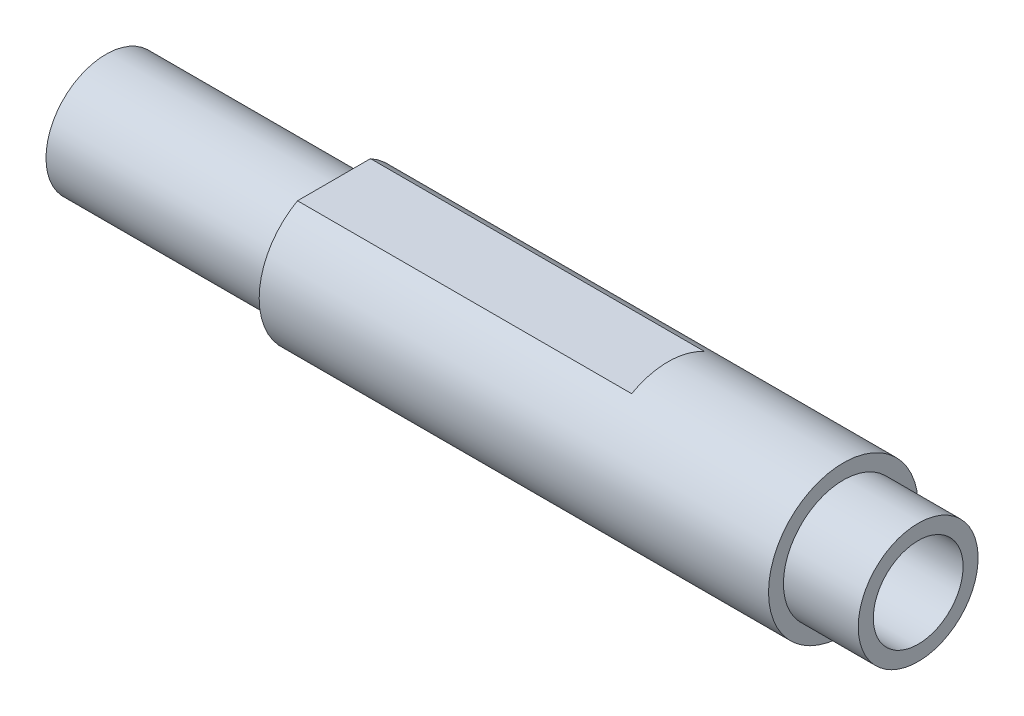
SolidWorks part; units mm, degrees
material "AISI 8620, Normalized steel"
ref_plane "Front Plane" through (0, 0, 0) normal (0, 0, 1) x (1, 0, 0)
ref_plane "Top Plane" through (0, 0, 0) normal (0, 1, 0) x (1, 0, 0)
ref_plane "Right Plane" through (0, 0, 0) normal (1, 0, 0) x (0, 0, -1)
sketch "Sketch6" plane through (0, 0, 0) normal (0, 0, 1) x (1, 0, 0)
  line L0 (-1000, 0) -> (49000, 0) construction
  line L1 (-38.276, 0) -> (-38.276, 4.005)
  line L2 (-38.276, 4.005) -> (-23.036, 4.005)
  line L3 (-23.036, 4.005) -> (-23.036, 5)
  line L4 (-23.036, 5) -> (11, 5)
  line L5 (11, 5) -> (11, 4.005)
  line L6 (11, 4.005) -> (16, 4.005)
  line L7 (16, 4.005) -> (16, 0)
  line L8 (16, 0) -> (-38.276, 0)
  line L9 (0, 0) -> (0, 26.6124) construction
  dimension "D1" = 34.036
  dimension "D2" = 4.005
  dimension "D3" = 5
  dimension "D4" = 4.005
  dimension "D5" = 15.24
  dimension "D6" = 5
  dimension "D7" = 16
revolve "Revolve1" add sketch "Sketch6" angle 360 about L0
sketch "Sketch7" plane through (11, 0, 0) normal (1, 0, 0) x (0, 0, -1)
  line L0 (0, 4.005) -> (-4.5829, 4.005)
  line L1 (-4.5829, 4.005) -> (-4.5829, 6.0691)
  line L2 (-4.5829, 6.0691) -> (4.4775, 6.0691)
  line L3 (4.4775, 6.0691) -> (4.4775, 4.005)
  line L4 (4.4775, 4.005) -> (0, 4.005)
  circle A2 centre (0, 0) radius 4.005 construction
  circle A3 centre (0, 0) radius 4.005 construction
ref_plane "Plane1" through (13.5, 0, 0) normal (1, 0, 0) x (0, 0, -1)
ref_plane "Plane2" through (-33.276, 0, 0) normal (-1, 0, 0) x (0, 0, 1)
sketch "Sketch8" plane through (0, 0, 0) normal (0, 1, 0) x (1, 0, 0)
  line L0 (-38.276, 4.005) -> (-38.276, -4.005) construction
  circle A0 centre (-35.276, 0) radius 1.5
  dimension "D2" = 3
  dimension "D1" = 3
extrude "Cut-Extrude2" cut sketch "Sketch8" against normal blind 10 contours A0
sketch "Sketch9" plane through (-38.276, 0, 0) normal (-1, 0, 0) x (0, 0, 1)
  circle A0 centre (0, 0) radius 3.17
extrude "Cut-Extrude3" cut sketch "Sketch9" against normal blind 7
sketch "Sketch10" plane through (16, 0, 0) normal (1, 0, 0) x (0, 0, -1)
  circle A0 centre (0, 0) radius 3
extrude "Cut-Extrude4" cut sketch "Sketch10" against normal blind 32.5
sketch "Sketch11" plane through (-23.036, 0, 0) normal (-1, 0, 0) x (0, 0, 1)
  circle A0 centre (0, 0) radius 4.005
  circle A1 centre (0, 0) radius 5
extrude "Boss-Extrude1" [suppressed] add sketch "Sketch11" along normal blind 5.08
sketch "Sketch12" plane through (0, 0, 0) normal (0, 0, 1) x (1, 0, 0)
  line L0 (11, 5) -> (-23.036, 5) construction
  line L1 (-25.511, 9.5012) -> (-0.7078, 9.5012)
  line L2 (-25.511, 9.5012) -> (-25.511, 4.365)
  line L3 (-25.511, 4.365) -> (-0.7078, 4.365)
  line L4 (-0.7078, 9.5012) -> (-0.7078, 4.365)
  dimension "D1" = 5.1362
  dimension "D2" = 0.635
extrude "Cut-Extrude5" cut sketch "Sketch12" against normal mid plane 25.4
